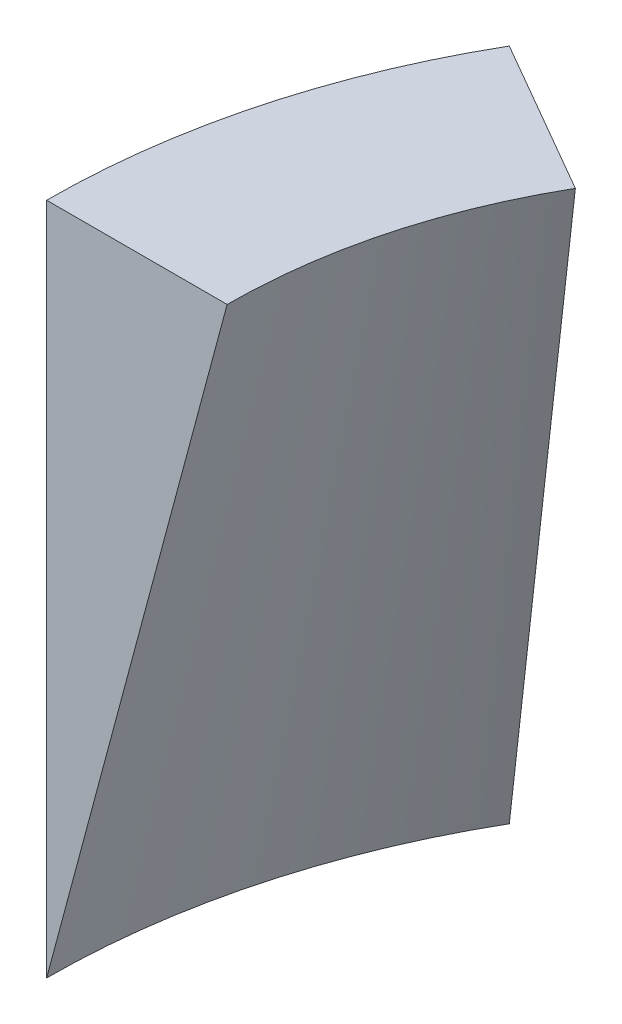
SolidWorks part; units mm, degrees
ref_plane "Front Plane" through (0, 0, 0) normal (0, 0, 1) x (1, 0, 0)
ref_plane "Top Plane" through (0, 0, 0) normal (0, 1, 0) x (1, 0, 0)
ref_plane "Right Plane" through (0, 0, 0) normal (1, 0, 0) x (0, 0, -1)
sketch "Sketch1" plane through (0, 0, 0) normal (0, 0, 1) x (1, 0, 0)
  line L0 (0, 0) -> (1.8894, 7.0513)
  line L1 (1.8894, 7.0513) -> (0, 7.0513)
  line L2 (0, 7.0513) -> (0, 0)
  line L3 (1.8894, 7.0513) -> (1.8894, 0.1467) construction
  line L4 (1.8894, 0.1467) -> (1.8894, -0.4479) construction
  line L5 (1.8894, 7.0513) -> (7.6394, 7.0513) construction
  line L6 (7.6394, 7.0513) -> (7.6394, -1.2984) construction
  dimension "D1" = 15
  dimension "D2" = 7.3
  dimension "D3" = 5.75
sketch "Sketch2" plane through (0, 0, 0) normal (0, 1, 0) x (1, 0, 0)
  circle A0 centre (7.6394, 0) radius 5.75
  dimension "D2" = 11.5
  dimension "D1" = 7.6394
revolve "Revolve1" add sketch "Sketch1" angle 30 about L6
